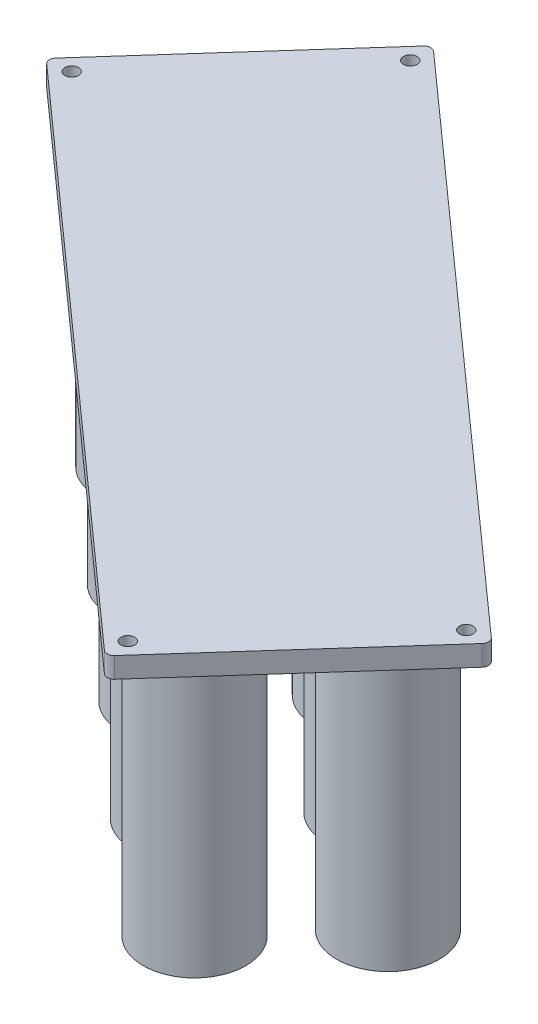
SolidWorks part; units mm, degrees
ref_plane "前视基准面" through (0, 0, 0) normal (0, 0, 1) x (1, 0, 0)
ref_plane "上视基准面" through (0, 0, 0) normal (0, 1, 0) x (1, 0, 0)
ref_plane "右视基准面" through (0, 0, 0) normal (1, 0, 0) x (0, 0, -1)
other "Configuration Table"
ref_plane "基准面1" through (0, -9.6938, 0) normal (0, -1, 0) x (1, 0, 0)
sketch "草图1" plane through (0, -9.6938, 0) normal (0, -1, 0) x (1, 0, 0)
  line L0 (-36.6177, 41.9099) -> (-9.9843, 12.0659)
  line L1 (-9.9843, 12.0659) -> (69.8484, 83.3101)
  line L2 (69.8484, 83.3101) -> (43.215, 113.1541)
  line L3 (43.215, 113.1541) -> (-36.6177, 41.9099)
extrude "凸台-拉伸1" add sketch "草图1" against normal blind 3
ref_plane "基准面2" through (0, 0, 68.1328) normal (0, 0, -1) x (-1, 0, 0)
sketch "草图2" plane through (0, 0, 68.1328) normal (0, 0, -1) x (-1, 0, 0)
  line L0 (-45.3226, -39.6938) -> (-37.8226, -39.6938)
  line L1 (-37.8226, -39.6938) -> (-37.8226, -9.6938)
  line L2 (-37.8226, -9.6938) -> (-45.3226, -9.6938)
  line L3 (-45.3226, -9.6938) -> (-45.3226, -39.6938)
  line L4 (-37.8226, -39.6938) -> (-37.8226, -9.6938) construction
revolve "旋转1" add sketch "草图2" angle 360 about L4
ref_plane "基准面3" through (0, 0, 83.0548) normal (0, 0, -1) x (-1, 0, 0)
sketch "草图3" plane through (0, 0, 83.0548) normal (0, 0, -1) x (-1, 0, 0)
  line L0 (-32.006, -39.6938) -> (-24.506, -39.6938)
  line L1 (-24.506, -39.6938) -> (-24.506, -9.6938)
  line L2 (-24.506, -9.6938) -> (-32.006, -9.6938)
  line L3 (-32.006, -9.6938) -> (-32.006, -39.6938)
  line L4 (-24.506, -39.6938) -> (-24.506, -9.6938) construction
revolve "旋转2" add sketch "草图3" angle 360 about L4
ref_plane "基准面4" through (0, 0, 97.0373) normal (0, 0, -1) x (-1, 0, 0)
sketch "草图4" plane through (0, 0, 97.0373) normal (0, 0, -1) x (-1, 0, 0)
  line L0 (-47.6741, -39.6938) -> (-40.1741, -39.6938)
  line L1 (-40.1741, -39.6938) -> (-40.1741, -9.6938)
  line L2 (-40.1741, -9.6938) -> (-47.6741, -9.6938)
  line L3 (-47.6741, -9.6938) -> (-47.6741, -39.6938)
  line L4 (-40.1741, -39.6938) -> (-40.1741, -9.6938) construction
revolve "旋转3" add sketch "草图4" angle 360 about L4
ref_plane "基准面5" through (0, 0, 82.1153) normal (0, 0, -1) x (-1, 0, 0)
sketch "草图5" plane through (0, 0, 82.1153) normal (0, 0, -1) x (-1, 0, 0)
  line L0 (-60.9907, -39.6938) -> (-53.4907, -39.6938)
  line L1 (-53.4907, -39.6938) -> (-53.4907, -9.6938)
  line L2 (-53.4907, -9.6938) -> (-60.9907, -9.6938)
  line L3 (-60.9907, -9.6938) -> (-60.9907, -39.6938)
  line L4 (-53.4907, -39.6938) -> (-53.4907, -9.6938) construction
revolve "旋转4" add sketch "草图5" angle 360 about L4
ref_plane "基准面6" through (0, 0, 69.0723) normal (0, 0, -1) x (-1, 0, 0)
sketch "草图6" plane through (0, 0, 69.0723) normal (0, 0, -1) x (-1, 0, 0)
  line L0 (-16.3379, -39.6938) -> (-8.8379, -39.6938)
  line L1 (-8.8379, -39.6938) -> (-8.8379, -9.6938)
  line L2 (-8.8379, -9.6938) -> (-16.3379, -9.6938)
  line L3 (-16.3379, -9.6938) -> (-16.3379, -39.6938)
  line L4 (-8.8379, -39.6938) -> (-8.8379, -9.6938) construction
revolve "旋转5" add sketch "草图6" angle 360 about L4
ref_plane "基准面7" through (0, 0, 55.0898) normal (0, 0, -1) x (-1, 0, 0)
sketch "草图7" plane through (0, 0, 55.0898) normal (0, 0, -1) x (-1, 0, 0)
  line L0 (-0.6698, -39.6938) -> (6.8302, -39.6938)
  line L1 (6.8302, -39.6938) -> (6.8302, -9.6938)
  line L2 (6.8302, -9.6938) -> (-0.6698, -9.6938)
  line L3 (-0.6698, -9.6938) -> (-0.6698, -39.6938)
  line L4 (6.8302, -39.6938) -> (6.8302, -9.6938) construction
revolve "旋转6" add sketch "草图7" angle 360 about L4
ref_plane "基准面8" through (0, 0, 41.1073) normal (0, 0, -1) x (-1, 0, 0)
sketch "草图8" plane through (0, 0, 41.1073) normal (0, 0, -1) x (-1, 0, 0)
  line L0 (14.9984, -39.6938) -> (22.4984, -39.6938)
  line L1 (22.4984, -39.6938) -> (22.4984, -9.6938)
  line L2 (22.4984, -9.6938) -> (14.9984, -9.6938)
  line L3 (14.9984, -9.6938) -> (14.9984, -39.6938)
  line L4 (22.4984, -39.6938) -> (22.4984, -9.6938) construction
revolve "旋转7" add sketch "草图8" angle 360 about L4
ref_plane "基准面9" through (0, 0, 54.1503) normal (0, 0, -1) x (-1, 0, 0)
sketch "草图9" plane through (0, 0, 54.1503) normal (0, 0, -1) x (-1, 0, 0)
  line L0 (-29.6545, -39.6938) -> (-22.1545, -39.6938)
  line L1 (-22.1545, -39.6938) -> (-22.1545, -9.6938)
  line L2 (-22.1545, -9.6938) -> (-29.6545, -9.6938)
  line L3 (-29.6545, -9.6938) -> (-29.6545, -39.6938)
  line L4 (-22.1545, -39.6938) -> (-22.1545, -9.6938) construction
revolve "旋转8" add sketch "草图9" angle 360 about L4
ref_plane "基准面10" through (0, 0, 40.1678) normal (0, 0, -1) x (-1, 0, 0)
sketch "草图10" plane through (0, 0, 40.1678) normal (0, 0, -1) x (-1, 0, 0)
  line L0 (-13.9864, -39.6938) -> (-6.4864, -39.6938)
  line L1 (-6.4864, -39.6938) -> (-6.4864, -9.6938)
  line L2 (-6.4864, -9.6938) -> (-13.9864, -9.6938)
  line L3 (-13.9864, -9.6938) -> (-13.9864, -39.6938)
  line L4 (-6.4864, -39.6938) -> (-6.4864, -9.6938) construction
revolve "旋转9" add sketch "草图10" angle 360 about L4
ref_plane "基准面11" through (0, 0, 26.1853) normal (0, 0, -1) x (-1, 0, 0)
sketch "草图11" plane through (0, 0, 26.1853) normal (0, 0, -1) x (-1, 0, 0)
  line L0 (1.6817, -39.6938) -> (9.1817, -39.6938)
  line L1 (9.1817, -39.6938) -> (9.1817, -9.6938)
  line L2 (9.1817, -9.6938) -> (1.6817, -9.6938)
  line L3 (1.6817, -9.6938) -> (1.6817, -39.6938)
  line L4 (9.1817, -39.6938) -> (9.1817, -9.6938) construction
revolve "旋转10" add sketch "草图11" angle 360 about L4
hole_wizard "Ø2.0 (2) 直径孔1" positions "草图13" profile "草图12" hole size "Ø2.0" standard "ANSI Metric"
sketch "草图13" plane through (0, -9.6938, 0) normal (0, -1, 0) x (-1, 0, 0)
  point P0 (-43.0144, -109.6243)
  point P1 (9.7837, -15.5958)
  point P2 (33.0879, -41.7093)
  point P3 (-66.3185, -83.5108)
sketch "草图12" plane through (43.0144, -9.6938, 109.6243) normal (1, 0, 0) x (0, 0, -1)
  line L0 (0, 0) -> (0, 3)
  line L1 (0, 3) -> (1, 3)
  line L2 (1, 3) -> (1, 0)
  line L5 (1, 0) -> (0, 0)
  line L11 (0, -6.35) -> (0, 107.95) construction
  dimension "通孔孔直径" = 2
  dimension "通孔孔深度" = 3
fillet "圆角1" radius 1 4 edges at (43.215, -8.1938, 113.1541) (69.8484, -8.1938, 83.3101) (-9.9843, -8.1938, 12.0659) (-36.6177, -8.1938, 41.9099)
sketch "草图14" plane through (0, -39.6938, 0) normal (0, -1, 0) x (1, 0, 0)
  circle A0 centre (40.1741, 97.0373) radius 7.5
  circle A1 centre (24.506, 83.0548) radius 7.5
  circle A2 centre (8.8379, 69.0723) radius 7.5
  circle A3 centre (-6.8302, 55.0898) radius 7.5
  circle A4 centre (-22.4984, 41.1073) radius 7.5
  circle A5 centre (-9.1817, 26.1853) radius 7.5
  circle A6 centre (6.4864, 40.1678) radius 7.5
  circle A7 centre (22.1545, 54.1503) radius 7.5
  circle A8 centre (37.8226, 68.1328) radius 7.5
  circle A9 centre (53.4907, 82.1153) radius 7.5
extrude "凸台-拉伸2" add sketch "草图14" along normal blind 12
